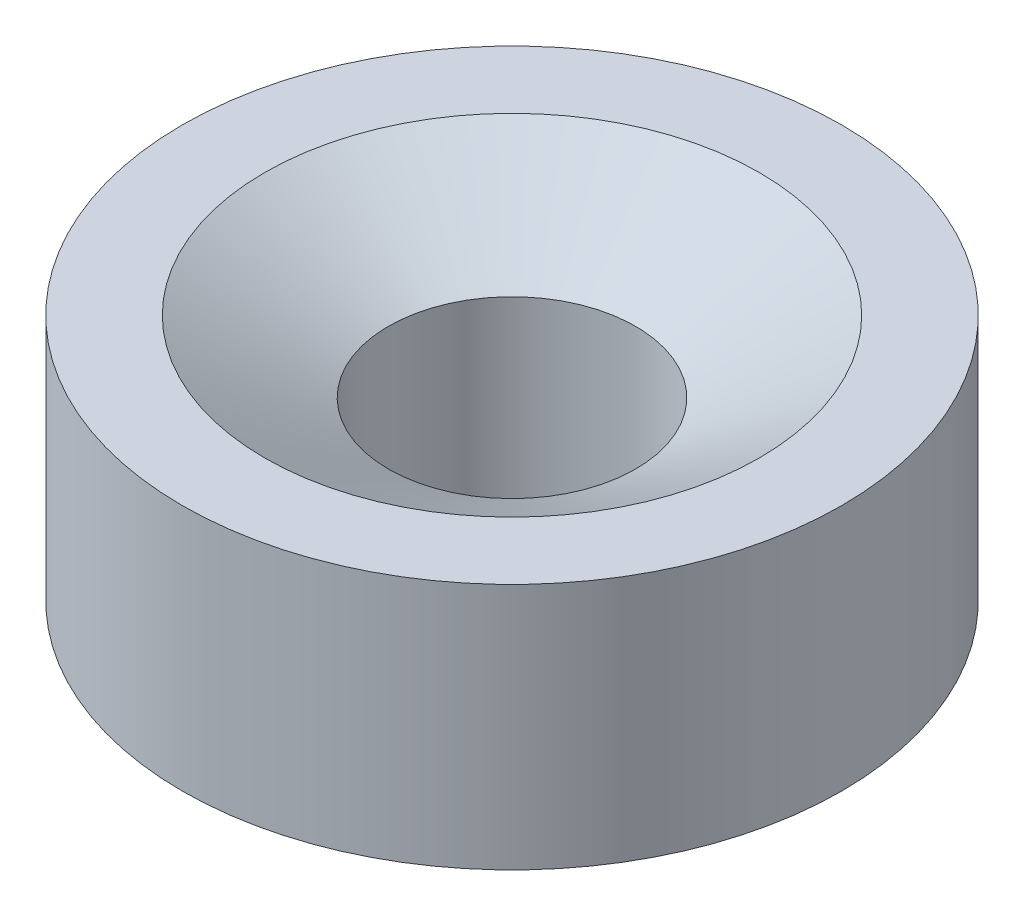
SolidWorks part; units mm, degrees
material "Nickel"
ref_plane "Front Plane" through (0, 0, 0) normal (0, 0, 1) x (1, 0, 0)
ref_plane "Top Plane" through (0, 0, 0) normal (0, 1, 0) x (1, 0, 0)
ref_plane "Right Plane" through (0, 0, 0) normal (1, 0, 0) x (0, 0, -1)
sketch "Sketch1" plane through (0, 0, 0) normal (0, 1, 0) x (1, 0, 0)
  circle A0 centre (0, 0) radius 4
  circle A1 centre (0, 0) radius 1.5
  dimension "D1" = 8
  dimension "D2" = 3
extrude "Boss-Extrude1" add sketch "Sketch1" along normal blind 3
chamfer "Chamfer1" distance 1.5 angle 30 1 edges at (0, 3, 1.5)
